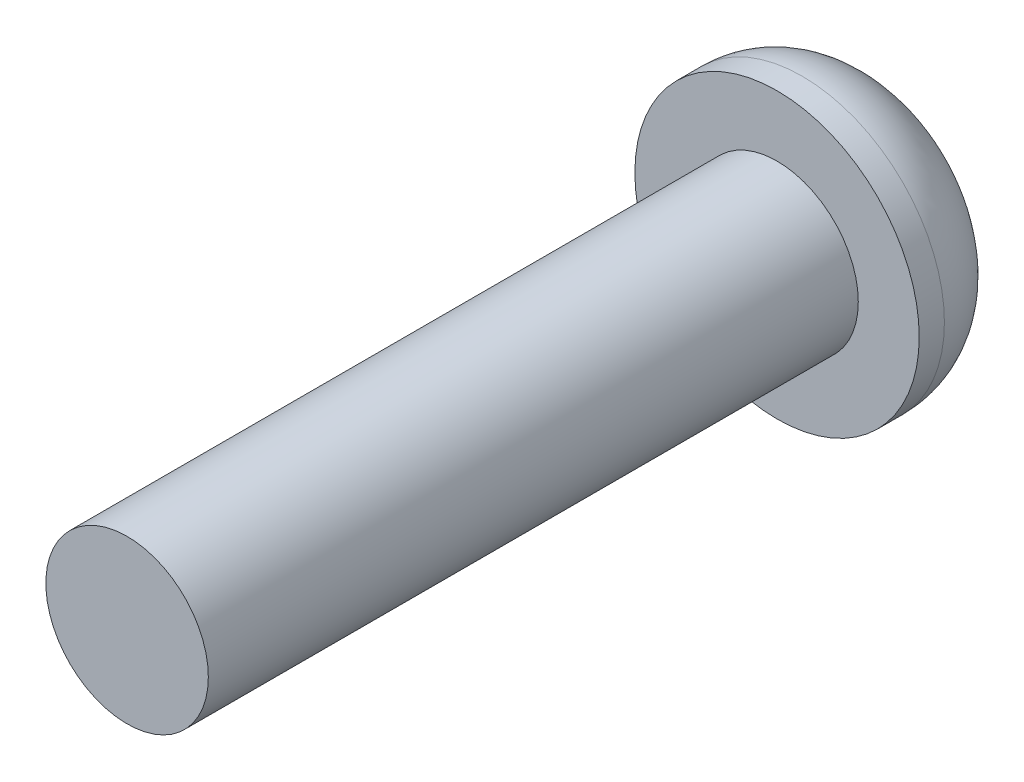
SolidWorks part; units mm, degrees
ref_plane "前视基准面" through (0, 0, 0) normal (0, 0, 1) x (1, 0, 0)
ref_plane "上视基准面" through (0, 0, 0) normal (0, 1, 0) x (1, 0, 0)
ref_plane "右视基准面" through (0, 0, 0) normal (1, 0, 0) x (0, 0, -1)
sketch "草图1" plane through (0, 0, 0) normal (0, 0, 1) x (1, 0, 0)
  circle A0 centre (0, 0) radius 1
  dimension "D1" = 2
extrude "凸台-拉伸1" add sketch "草图1" along normal blind 8
sketch "草图2" plane through (0, 0, 0) normal (0, 0, -1) x (-1, 0, 0)
  circle A0 centre (0, 0) radius 1.75
  point P3 (0, 0)
  dimension "D1" = 3.5
extrude "凸台-拉伸2" add sketch "草图2" along normal blind 1.31
fillet "圆角2" radius 1 1 edges at (-1.75, 0, -1.31)
